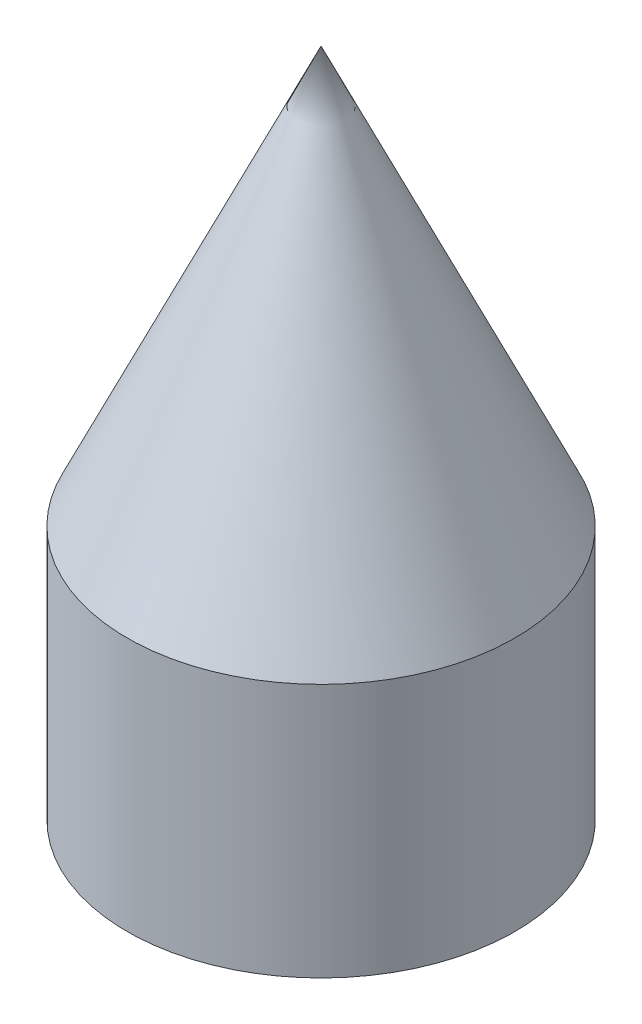
SolidWorks part; units mm, degrees
ref_plane "Face" through (0, 0, 0) normal (0, 0, 1) x (1, 0, 0)
ref_plane "Dessus" through (0, 0, 0) normal (0, 1, 0) x (1, 0, 0)
ref_plane "Droite" through (0, 0, 0) normal (1, 0, 0) x (0, 0, -1)
sketch "Esquisse1" plane through (0, 0, 0) normal (0, 0, 1) x (1, 0, 0)
  line L0 (3.1, 0) -> (3.1, 6)
  line L1 (3.1, 6) -> (0, 6)
  line L2 (0, 6) -> (0, 21.0815)
  line L3 (0, 21.0815) -> (6.1, 8)
  line L4 (6.1, 8) -> (6.1, 0)
  line L5 (6.1, 0) -> (3.1, 0)
  line L6 (0, 0) -> (0, 5.8269) construction
  dimension "D1" = 6.2
  dimension "D2" = 3
  dimension "D3" = 25
  dimension "D4" = 6
  dimension "D5" = 2
revolve "Révolution1" add sketch "Esquisse1" angle 360 about L6
